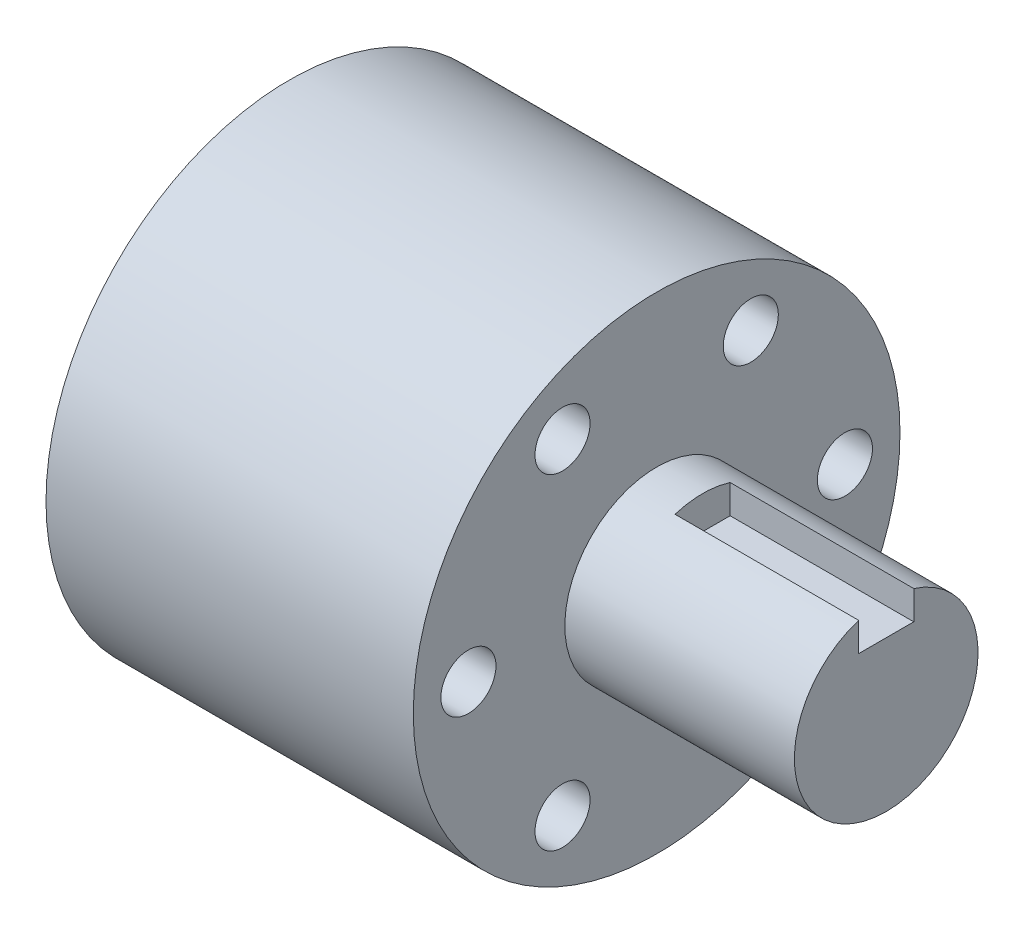
SolidWorks part; units mm, degrees
material "1.4000 (X6Cr13)"
ref_plane "前视基准面" through (0, 0, 0) normal (0, 0, 1) x (1, 0, 0)
ref_plane "上视基准面" through (0, 0, 0) normal (0, 1, 0) x (1, 0, 0)
ref_plane "右视基准面" through (0, 0, 0) normal (1, 0, 0) x (0, 0, -1)
sketch "草图1" plane through (0, 0, 0) normal (1, 0, 0) x (0, 0, -1)
  circle A0 centre (0, 0) radius 13.25
  dimension "D1" = 26.5
extrude "凸台-拉伸1" add sketch "草图1" along normal blind 20
sketch "草图2" plane through (20, 0, 0) normal (1, 0, 0) x (0, 0, -1)
  circle A1 centre (10.25, 0) radius 1.5
  circle A2 centre (5.125, -8.8768) radius 1.5
  circle A3 centre (-5.125, -8.8768) radius 1.5
  circle A4 centre (-10.25, 0) radius 1.5
  circle A5 centre (-5.125, 8.8768) radius 1.5
  circle A6 centre (5.125, 8.8768) radius 1.5
  point P18 (0, 0)
  dimension "D2" = 3
  dimension "D3" = 6
extrude "切除-拉伸1" cut sketch "草图2" against normal blind 5
sketch "草图3" plane through (20, 0, 0) normal (1, 0, 0) x (0, 0, -1)
  circle A0 centre (0, 0) radius 5
  dimension "D1" = 10
extrude "凸台-拉伸2" add sketch "草图3" along normal blind 12.5
sketch "草图4" plane through (32.5, 0, 0) normal (1, 0, 0) x (0, 0, -1)
  line L1 (-1.5, 3.2) -> (1.5, 3.2)
  line L2 (1.5, 3.2) -> (1.5, 4.7697)
  line L3 (-1.5, 3.2) -> (-1.5, 4.7697)
  circle A0 centre (0, 0) radius 5 construction
  arc A1 (1.5, 4.7697) -> (-1.5, 4.7697) centre (0, 0) ccw
extrude "切除-拉伸2" cut sketch "草图4" against normal blind 10
